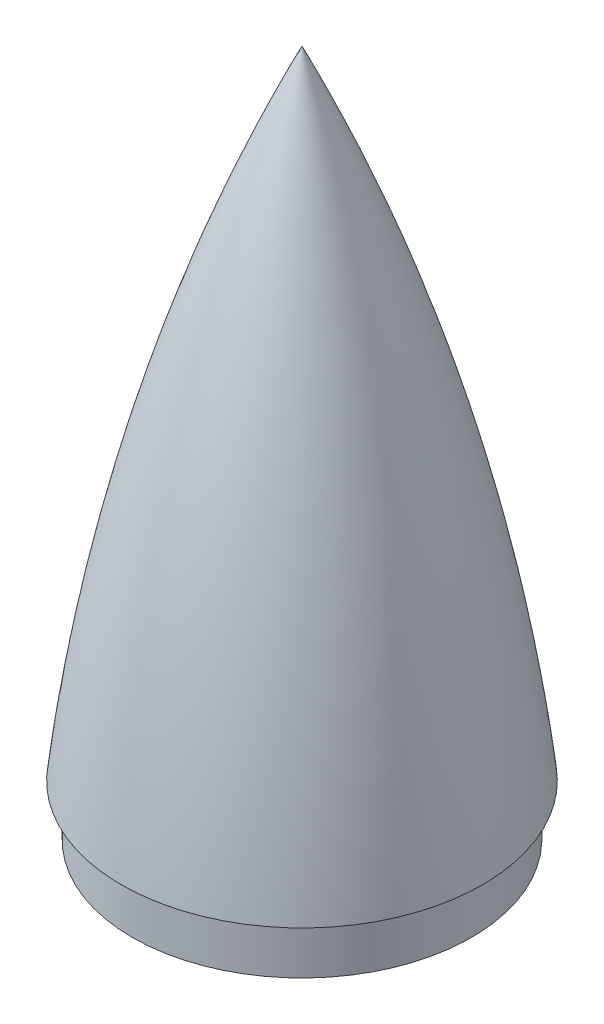
SolidWorks part; units mm, degrees
ref_plane "Front Plane" through (0, 0, 0) normal (0, 0, 1) x (1, 0, 0)
ref_plane "Top Plane" through (0, 0, 0) normal (0, 1, 0) x (1, 0, 0)
ref_plane "Right Plane" through (0, 0, 0) normal (1, 0, 0) x (0, 0, -1)
sketch "Croquis1" plane through (0, 0, 0) normal (1, 0, 0) x (0, 0, -1)
  line L0 (0, 0) -> (0, 290) construction
  line L1 (50, 12) -> (50, 103.2346)
  line L3 (55, 40) -> (55, 0)
  line L4 (55, 0) -> (50, 0)
  line L5 (55, 40) -> (56.8, 40)
  line L6 (0, 290) -> (0, 282.879)
  line L7 (50, 0) -> (0, 0)
  line L8 (0, 0) -> (0, 12)
  line L9 (0, 12) -> (50, 12)
  arc A0 (56.8, 40) -> (0, 290) centre (-538.8692, 36.1164) ccw
  arc A1 (50, 103.2346) -> (0, 282.879) centre (-538.8692, 36.1164) ccw
  arc A2 (53.8001, 39.9804) -> (-2.7139, 288.7214) centre (-538.8692, 36.1164) ccw construction
  dimension "D7" = 595.6818
  dimension "D1" = 110
  dimension "D2" = 1.8
  dimension "D3" = 5
  dimension "D4" = 250
  dimension "D5" = 40
  dimension "D8" = 12
  dimension "D6" = 3
revolve "Revolución1" add sketch "Croquis1" angle 360 about L0
ref_plane "Plano1" through (0, 103.2346, 0) normal (0, -1, 0) x (-1, 0, 0)
sketch "Croquis3" plane through (0, 103.2346, 0) normal (0, -1, 0) x (-1, 0, 0)
  circle A0 centre (0, 0) radius 68.8953
extrude "Cortar-Extruir3" cut sketch "Croquis3" along normal through all
sketch "Croquis4" plane through (0, 103.2346, 0) normal (0, -1, 0) x (1, 0, 0)
  circle A1 centre (0, 0) radius 50 construction
  circle A2 centre (0, 0) radius 50
  circle A3 centre (0, 0) radius 47
  dimension "D1" = 3
extrude "Saliente-Extruir2" add sketch "Croquis4" against normal up to surface up to face at (0, 103.2346, -50)
sketch "Croquis5" plane through (0, 103.2346, 0) normal (0, -1, 0) x (1, 0, 0)
  circle A1 centre (0, 0) radius 49.8
  circle A2 centre (0, 0) radius 47
  circle A3 centre (0, 0) radius 47
  dimension "D1" = 0
extrude "Saliente-Extruir3" add sketch "Croquis5" along normal blind 15
equation "\"R\"= ( \"L\" ^ 2 + \"Rn\" ^ 2 ) / ( 2 * \"Rn\" )"
equation "\"D7@Croquis1\"=\"R\""
equation "\"L\"=250"
equation "\"D4@Croquis1\"=\"L\""
equation "\"Diameter\"=110"
equation "\"D1@Croquis1\"=\"Diameter\""
equation "\"Rn\"= \"Diameter\" / 2"
